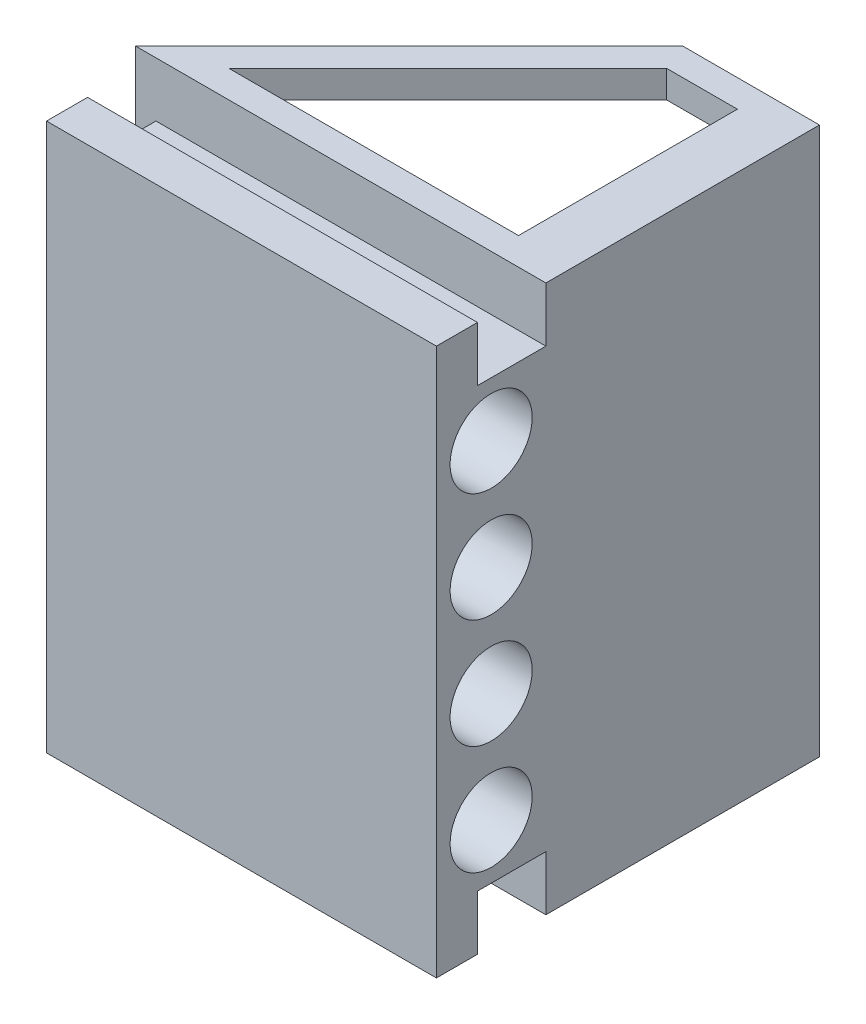
SolidWorks part; units mm, degrees
ref_plane "Front Plane" through (0, 0, 0) normal (0, 0, 1) x (1, 0, 0)
ref_plane "Top Plane" through (0, 0, 0) normal (0, 1, 0) x (1, 0, 0)
ref_plane "Right Plane" through (0, 0, 0) normal (1, 0, 0) x (0, 0, -1)
sketch "Sketch1" plane through (0, 0, 0) normal (0, 1, 0) x (1, 0, 0)
  line L0 (-17.3516, 20.3127) -> (-57.3516, -19.6873)
  line L1 (-17.3516, 20.3127) -> (2.6484, 20.3127)
  line L2 (-17.3516, 20.3127) -> (-17.3516, -19.6873)
  line L3 (-17.3516, -19.6873) -> (2.6484, -19.6873)
  line L4 (2.6484, 20.3127) -> (2.6484, -19.6873)
  line L5 (-57.3516, -19.6873) -> (-17.3516, -19.6873)
  dimension "D1" = 20
  dimension "D2" = 40
  dimension "D3" = 40
extrude "Boss-Extrude1" add sketch "Sketch1" against normal blind 80 contours L0 L5 L2 | L4 L1 L2 L3
sketch "Sketch8" plane through (2.6484, 0, 0) normal (1, 0, 0) x (0, 0, -1)
  line L0 (-19.6873, -80) -> (-19.6873, 0) construction
  line L14 (-19.6873, -8) -> (-35.6873, -8)
  line L15 (-19.6873, -8) -> (-19.6873, -72)
  line L16 (-19.6873, -72) -> (-35.6873, -72)
  line L17 (-35.6873, -8) -> (-35.6873, -72)
  dimension "D2" = 64
  dimension "D3" = 8
  dimension "D12" = 16
extrude "Boss-Extrude2" add sketch "Sketch8" against normal blind 57
sketch "Sketch12" plane through (0, -72, 0) normal (0, -1, 0) x (1, 0, 0)
  line L0 (2.6484, 35.6873) -> (2.6484, 19.6873) construction
  line L1 (-54.3516, 35.6873) -> (2.6484, 35.6873)
  line L2 (-54.3516, 35.6873) -> (-54.3516, 29.6873)
  line L3 (-54.3516, 29.6873) -> (2.6484, 29.6873)
  line L4 (2.6484, 35.6873) -> (2.6484, 29.6873)
  dimension "D1" = 6
sketch "Sketch10" plane through (2.6484, 0, 0) normal (1, 0, 0) x (0, 0, -1)
  line L8 (-27.6873, -8) -> (-27.6873, -72) construction
  line L9 (-19.6873, -8) -> (-35.6873, -8) construction
  line L10 (-35.6873, -72) -> (-19.6873, -72) construction
  circle A0 centre (-27.6873, -16) radius 6
  circle A4 centre (-27.6873, -32) radius 6
  circle A5 centre (-27.6873, -64) radius 6
  circle A6 centre (-27.6873, -48) radius 6
  dimension "D1" = 12
  dimension "D2" = 8
extrude "Cut-Extrude1" cut sketch "Sketch10" against normal blind 51
sketch "Sketch11" plane through (0, 0, 0) normal (0, 1, 0) x (1, 0, 0)
  line L0 (-47.6948, -15.6873) -> (-15.6948, 16.3127)
  line L1 (-15.6948, 16.3127) -> (-5.3516, 16.3127)
  line L2 (-5.3516, 16.3127) -> (-5.3516, -15.6873)
  line L3 (-5.3516, -15.6873) -> (-47.6948, -15.6873)
  line L4 (-54.3516, -19.6873) -> (2.6484, -19.6873) construction
  line L6 (2.6484, 20.3127) -> (2.6484, -19.6873) construction
  line L7 (-17.3516, 20.3127) -> (2.6484, 20.3127) construction
  line L8 (-17.3516, 20.3127) -> (-57.3516, -19.6873) construction
  dimension "D1" = 4
  dimension "D2" = 8
  dimension "D3" = 4
  dimension "D4" = 4
extrude "Cut-Extrude2" cut sketch "Sketch11" against normal through all
extrude "Boss-Extrude3" add sketch "Sketch12" along normal blind 8
sketch "Sketch14" plane through (0, -8, 0) normal (0, 1, 0) x (1, 0, 0)
  line L0 (2.6484, -19.6873) -> (2.6484, -35.6873) construction
  line L1 (-54.3516, -35.6873) -> (2.6484, -35.6873)
  line L2 (-54.3516, -35.6873) -> (-54.3516, -29.6873)
  line L3 (-54.3516, -29.6873) -> (2.6484, -29.6873)
  line L4 (2.6484, -35.6873) -> (2.6484, -29.6873)
  dimension "D1" = 6
extrude "Boss-Extrude4" add sketch "Sketch14" along normal blind 8
sketch "Sketch17" plane through (0, 0, -20.3127) normal (0, 0, -1) x (-1, 0, 0)
  line L0 (17.3516, 0) -> (57.3516, 0) construction
  line L1 (5.3516, -4) -> (53.3516, -4)
  line L2 (5.3516, -4) -> (5.3516, -76)
  line L3 (5.3516, -76) -> (53.3516, -76)
  line L4 (53.3516, -4) -> (53.3516, -76)
  line L5 (17.3516, -80) -> (57.3516, -80) construction
  line L6 (57.3516, -80) -> (57.3516, 0) construction
  line L7 (-2.6484, -80) -> (-2.6484, 0) construction
  dimension "D1" = 4
  dimension "D2" = 4
  dimension "D3" = 4
  dimension "D4" = 8
extrude "Cut-Extrude4" cut sketch "Sketch17" against normal blind 36
